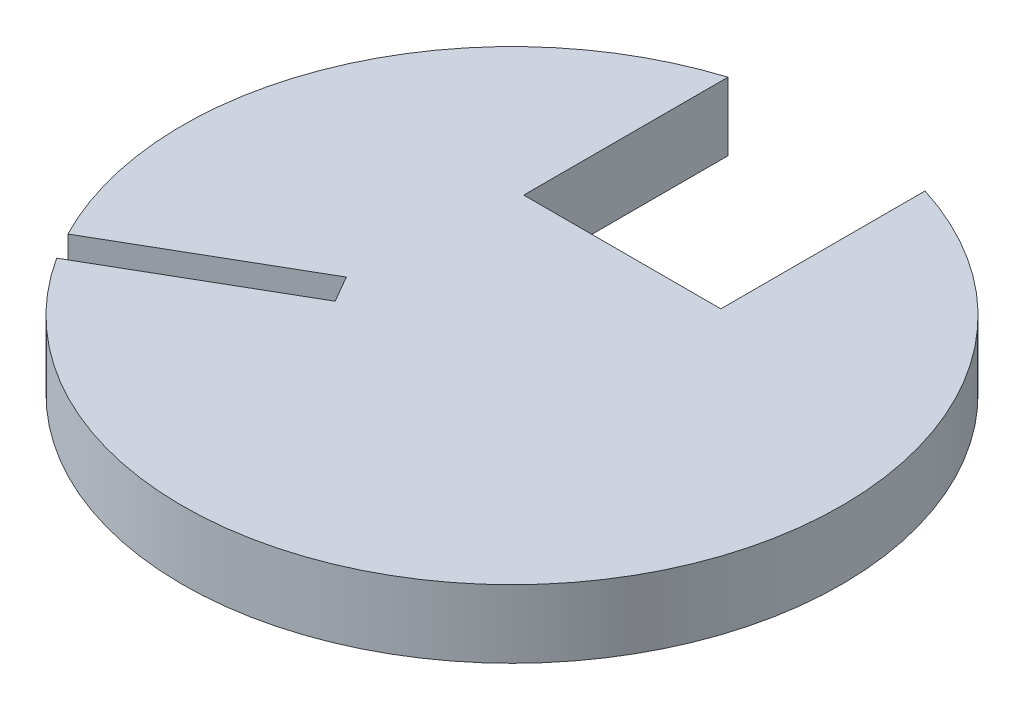
SolidWorks part; units mm, degrees
material "Acrylic (Medium-high impact)"
ref_plane "Front Plane" through (0, 0, 0) normal (0, 0, 1) x (1, 0, 0)
ref_plane "Top Plane" through (0, 0, 0) normal (0, 1, 0) x (1, 0, 0)
ref_plane "Right Plane" through (0, 0, 0) normal (1, 0, 0) x (0, 0, -1)
sketch "스케치1" plane through (0, 0, 0) normal (0, 1, 0) x (1, 0, 0)
  line L0 (0, -0.23) -> (0, 0) construction
  line L1 (-4.4475, -1.27) -> (4.4475, -1.27) construction
  line L2 (-4.4475, -1.27) -> (-4.4475, 1.27) construction
  line L3 (-4.4475, 1.27) -> (4.4475, 1.27) construction
  line L4 (4.4475, -1.27) -> (4.4475, 1.27) construction
  line L5 (-4.4475, -1.27) -> (4.4475, 1.27) construction
  line L6 (-4.4475, 1.27) -> (4.4475, -1.27) construction
  line L7 (-1.4475, -1.73) -> (1.4475, -1.73)
  line L8 (-1.4475, -1.73) -> (-1.4475, 1.27)
  line L9 (-1.4475, 1.27) -> (1.4475, 1.27) construction
  line L10 (1.4475, -1.73) -> (1.4475, 1.27)
  line L11 (-1.4475, -1.73) -> (1.4475, 1.27) construction
  line L12 (-1.4475, 1.27) -> (1.4475, -1.73) construction
  line L13 (1.4475, 1.27) -> (4.4475, 1.27) construction
  line L14 (-1.4475, 1.27) -> (-4.4475, 1.27) construction
  line L15 (0, -0.23) -> (0, -5.7175) construction
  arc A0 (-4.4475, -1.27) -> (4.4475, -1.27) centre (0, -1.27) ccw construction
  circle A1 centre (-2.6498, -5.6241) radius 0.6 construction
  circle A2 centre (2.6498, -5.6241) radius 0.6 construction
  circle A3 centre (0, -3.3503) radius 4.8417 construction
  arc A4 (-1.4475, 1.27) -> (1.4475, 1.27) centre (0, -3.3503) ccw
  point P1 (0, 0)
  point P7 (0, -0.23)
  dimension "D1" = 3
  dimension "D4" = 1.2
  dimension "D5" = 3
  dimension "D2" = 2.895
  dimension "D3" = 2.54
  dimension "D6" = 5.2995
extrude "보스-돌출1" add sketch "스케치1" along normal blind 1
sketch "스케치2" plane through (0, 1, 0) normal (0, 1, 0) x (1, 0, 0)
  line L0 (0, -3.3503) -> (-4.1931, -5.7712) construction
  line L1 (-4.0806, -5.966) -> (-4.3056, -5.5763)
  line L2 (-4.0806, -5.966) -> (-1.4825, -4.466)
  line L3 (-4.3056, -5.5763) -> (-1.7075, -4.0763)
  line L4 (-1.4825, -4.466) -> (-1.7075, -4.0763)
  line L5 (-4.0806, -5.966) -> (-1.7075, -4.0763) construction
  line L6 (-4.3056, -5.5763) -> (-1.4825, -4.466) construction
  line L7 (1.4475, -1.73) -> (-1.4475, -1.73) construction
  arc A0 (-1.4475, 1.27) -> (1.4475, 1.27) centre (0, -3.3503) ccw construction
  point P7 (-2.894, -5.0212)
  dimension "D1" = 3
  dimension "D2" = 0.45
  dimension "D3" = 30
extrude "컷-돌출1" cut sketch "스케치2" against normal up to surface (1 mm away) up to face at (0, 0, 2.5955)
